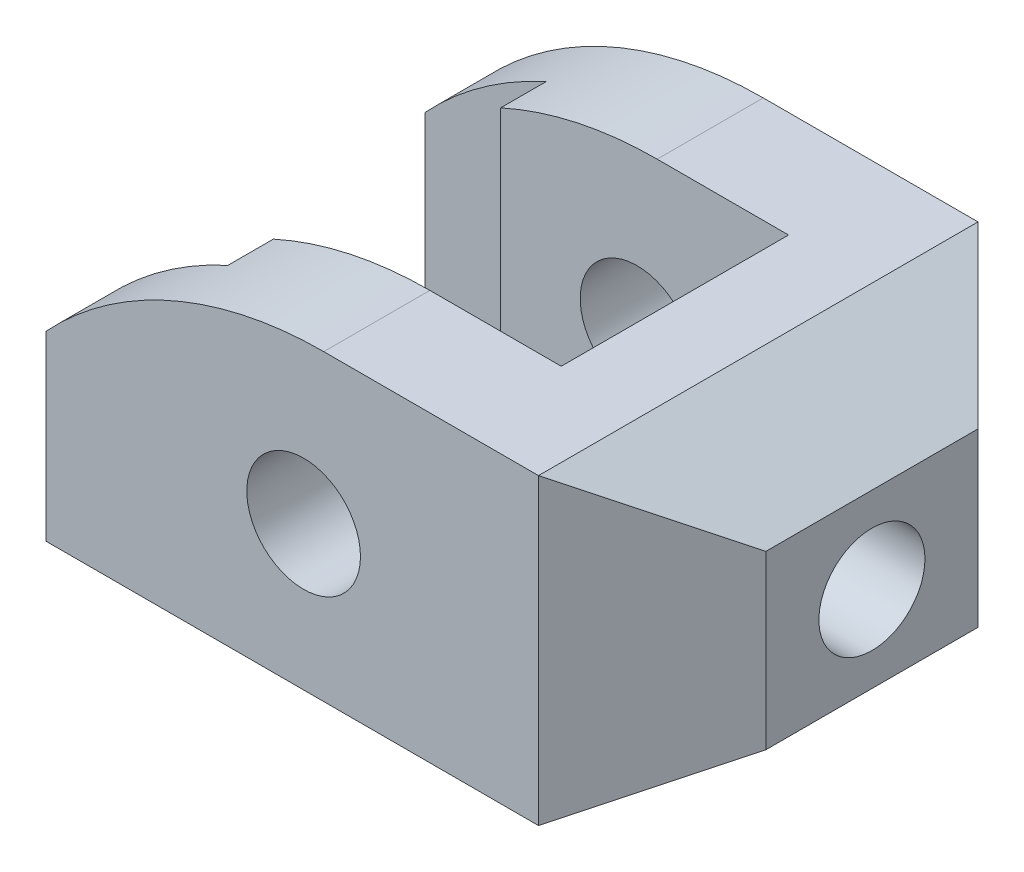
SolidWorks part; units mm, degrees
material "1060 Alloy"
ref_plane "Front Plane" through (0, 0, 0) normal (0, 0, 1) x (1, 0, 0)
ref_plane "Top Plane" through (0, 0, 0) normal (0, 1, 0) x (1, 0, 0)
ref_plane "Right Plane" through (0, 0, 0) normal (1, 0, 0) x (0, 0, -1)
sketch "Sketch1" plane through (0, 0, 0) normal (0, 1, 0) x (1, 0, 0)
  line L1 (40, -29) -> (-40, -29)
  line L2 (40, -29) -> (40, 29)
  line L3 (40, 29) -> (-40, 29)
  line L4 (-40, -29) -> (-40, 29)
  line L5 (40, -29) -> (-40, 29) construction
  line L6 (40, 29) -> (-40, -29) construction
  point P0 (0, 0)
  dimension "D1" = 58
  dimension "D2" = 80
extrude "Boss-Extrude1" add sketch "Sketch1" along normal blind 40
sketch "Sketch2" plane through (0, 0, 29) normal (0, 0, 1) x (1, 0, 0)
  line L0 (25, 40) -> (40, 40)
  line L1 (-40, 40) -> (40, 40) construction
  line L2 (40, 40) -> (40, 31.3397)
  line L3 (40, 40) -> (40, 0) construction
  line L4 (40, 31.3397) -> (25, 40)
  line L5 (-40, 19) -> (40, 19) construction
  line L7 (40, 0) -> (40, 8.6603)
  line L8 (40, 8.6603) -> (25, 0)
  line L9 (25, 0) -> (40, 0)
  line L11 (-40, 40) -> (-40, 0) construction
  line L12 (-40, 0) -> (40, 0) construction
  line L13 (-40, 0) -> (-40, 24)
  line L14 (-40, 24) -> (-40, 40)
  circle A0 centre (-6, 19) radius 7.5
  arc A3 (37.3914, 19) -> (-40, 24) centre (-3.3394, -10) ccw
  dimension "D4" = 15
  dimension "D7" = 15
  dimension "kd" = 100
  dimension "D1" = 15
  dimension "D2" = 30
  dimension "D3" = 19
  dimension "D5" = 31
  dimension "D6" = 24
  dimension "D8" = 65
  dimension "D9" = 30
  dimension "D11" = 40
extrude "Cut-Extrude1" cut sketch "Sketch2" against normal through all
sketch "Sketch3" plane through (0, 0, 0) normal (0, 1, 0) x (1, 0, 0)
  line L0 (-40, 0) -> (40, 0) construction
  line L1 (25, 29) -> (40, 29)
  line L2 (-40, 29) -> (-40, -29) construction
  line L3 (40, 29) -> (40, -29) construction
  line L4 (40, 29) -> (40, 14)
  line L5 (40, 14) -> (25, 29)
  line L6 (40, -14) -> (25, -29)
  line L7 (40, -29) -> (40, -14)
  line L8 (25, -29) -> (40, -29)
  line L9 (-40, 21) -> (-24, 21)
  line L10 (25, 29) -> (25, -29) construction
  line L11 (-24, 21) -> (-24, 15)
  line L12 (-24, 15) -> (14, 15)
  line L13 (14, 15) -> (14, -15)
  line L14 (-3.3394, 29) -> (-40, 29) construction
  line L15 (-24, -15) -> (14, -15)
  line L16 (-24, -21) -> (-24, -15)
  line L17 (-40, -21) -> (-24, -21)
  line L18 (-40, 21) -> (-40, -21)
  point P24 (14, 0)
  dimension "D1" = 45
  dimension "D2" = 8
  dimension "D3" = 6
  dimension "D4" = 16
  dimension "D5" = 11
extrude "Cut-Extrude6" cut sketch "Sketch3" along normal through all
sketch "Sketch4" plane through (40, 0, 0) normal (1, 0, 0) x (0, 0, -1)
  line L1 (14, 31.3397) -> (-14, 31.3397) construction
  line L2 (0, 31.3397) -> (0, 8.6603) construction
  line L3 (14, 8.6603) -> (-14, 8.6603) construction
  circle A0 centre (0, 20) radius 7
  dimension "D1" = 14
extrude "Cut-Extrude7" cut sketch "Sketch4" against normal through all
equation "\"a\"= 58mm"
equation "\"b\"= 40mm"
equation "\"c\"= 65mm"
